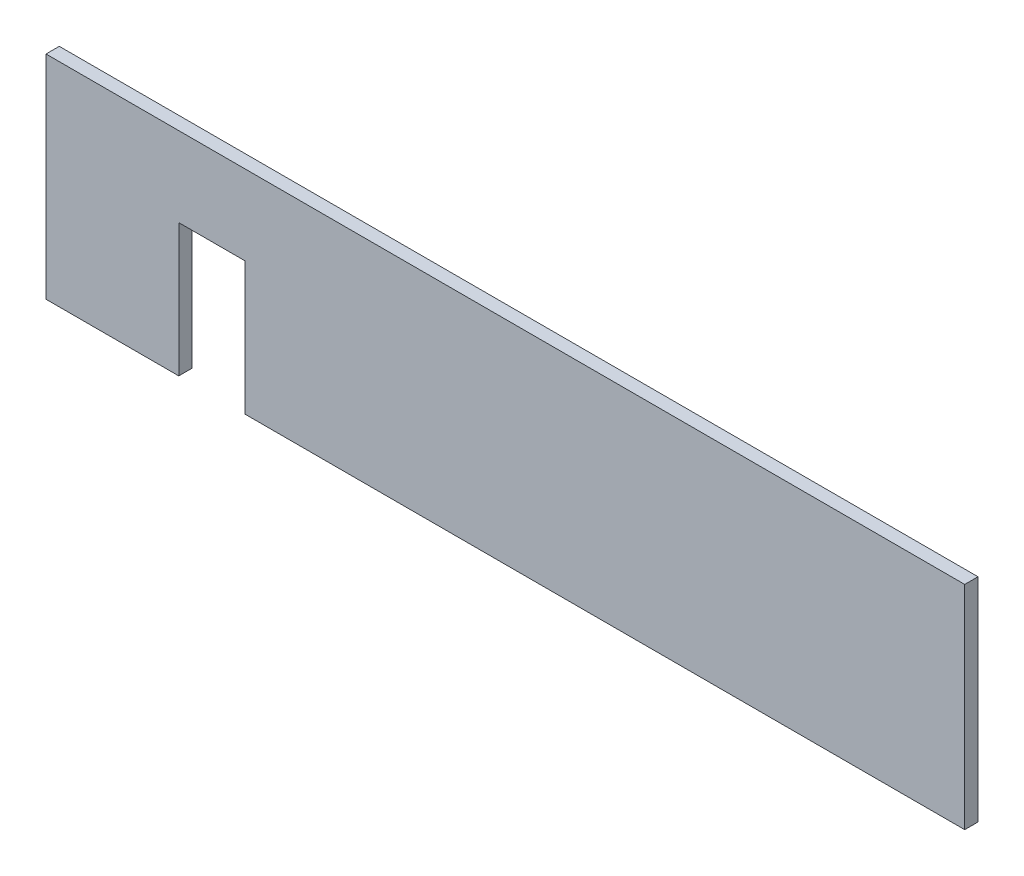
SolidWorks part; units mm, degrees
ref_plane "Front Plane" through (0, 0, 0) normal (0, 0, 1) x (1, 0, 0)
ref_plane "Top Plane" through (0, 0, 0) normal (0, 1, 0) x (1, 0, 0)
ref_plane "Right Plane" through (0, 0, 0) normal (1, 0, 0) x (0, 0, -1)
sketch "Sketch1" plane through (0, 0, 0) normal (0, 0, 1) x (1, 0, 0)
  line L0 (0, 0) -> (0, 50.8)
  line L1 (0, 50.8) -> (-219.71, 50.8)
  line L2 (-219.71, 50.8) -> (-219.71, 0)
  line L3 (-219.71, 0) -> (-187.96, 0)
  line L4 (-187.96, 0) -> (-187.96, 31.75)
  line L5 (-187.96, 31.75) -> (-172.085, 31.75)
  line L6 (-172.085, 31.75) -> (-172.085, 0)
  line L7 (-172.085, 0) -> (0, 0)
  dimension "D1" = 15.875
  dimension "D2" = 50.8
  dimension "D3" = 19.05
  dimension "D4" = 172.085
  dimension "D5" = 31.75
extrude "Boss-Extrude1" add sketch "Sketch1" along normal blind 3.175
equation "\"D1@Sketch1\"=5/8"
equation "\"D1@Boss-Extrude1\"=1/8"
